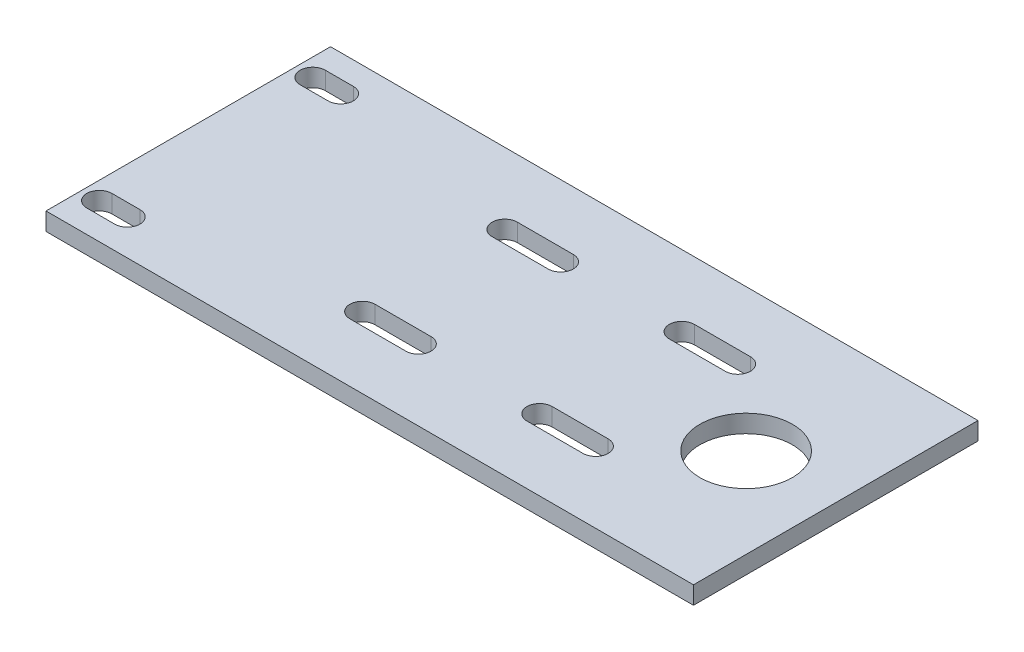
SolidWorks part; units mm, degrees
ref_plane "Front Plane" through (0, 0, 0) normal (0, 0, 1) x (1, 0, 0)
ref_plane "Top Plane" through (0, 0, 0) normal (0, 1, 0) x (1, 0, 0)
ref_plane "Right Plane" through (0, 0, 0) normal (1, 0, 0) x (0, 0, -1)
sketch "Sketch1" plane through (0, 0, 0) normal (0, 1, 0) x (1, 0, 0)
  line L0 (0, 50.8) -> (0, 0)
  line L1 (0, 0) -> (125, 0)
  line L3 (0, 50.8) -> (125, 50.8)
  line L4 (125, 0) -> (125, 50.8)
  dimension "D1" = 50.8
  dimension "D2" = 125
extrude "Boss-Extrude1" add sketch "Sketch1" along normal blind 3.175
sketch "Sketch2" plane through (0, 3.175, 0) normal (0, 1, 0) x (1, 0, 0)
  line L0 (125, 0) -> (125, 50.8) construction
  line L1 (125, 50.8) -> (0, 50.8) construction
  line L2 (125, 50.8) -> (0, 50.8) construction
  line L3 (0, 50.8) -> (0, 0) construction
  line L4 (99.6, 25.4) -> (80.425, 25.4) construction
  line L5 (80.425, 50.8) -> (80.425, 40.35) construction
  line L6 (0, 0) -> (125, 0) construction
  line L7 (3.175, 42.2) -> (8.175, 42.2)
  line L8 (3.175, 4.1) -> (8.175, 4.1)
  line L9 (3.175, 46.7) -> (8.175, 46.7)
  line L10 (3.175, 8.6) -> (8.175, 8.6)
  line L11 (80.425, 40.35) -> (85.425, 40.35)
  line L12 (80.425, 40.35) -> (75.425, 40.35)
  line L13 (48.8, 35.85) -> (43.8, 35.85)
  line L14 (48.8, 35.85) -> (53.8, 35.85)
  line L15 (48.8, 10.45) -> (43.8, 10.45)
  line L16 (48.8, 10.45) -> (53.8, 10.45)
  line L17 (48.8, 40.35) -> (43.8, 40.35)
  line L18 (48.8, 40.35) -> (53.8, 40.35)
  line L19 (48.8, 14.95) -> (43.8, 14.95)
  line L20 (48.8, 14.95) -> (53.8, 14.95)
  line L21 (80.425, 35.85) -> (85.425, 35.85)
  line L22 (80.425, 35.85) -> (75.425, 35.85)
  line L23 (80.425, 35.85) -> (80.425, 0) construction
  line L24 (80.425, 10.45) -> (75.425, 10.45)
  line L25 (80.425, 14.95) -> (75.425, 14.95)
  line L26 (80.425, 14.95) -> (85.425, 14.95)
  line L27 (80.425, 10.45) -> (85.425, 10.45)
  circle A0 centre (99.6, 25.4) radius 8.255
  arc A1 (3.175, 46.7) -> (3.175, 42.2) centre (3.175, 44.45) ccw
  arc A2 (3.175, 8.6) -> (3.175, 4.1) centre (3.175, 6.35) ccw
  arc A3 (8.175, 42.2) -> (8.175, 46.7) centre (8.175, 44.45) ccw
  arc A4 (8.175, 4.1) -> (8.175, 8.6) centre (8.175, 6.35) ccw
  arc A5 (43.8, 40.35) -> (43.8, 35.85) centre (43.8, 38.1) ccw
  arc A6 (43.8, 14.95) -> (43.8, 10.45) centre (43.8, 12.7) ccw
  arc A7 (75.425, 40.35) -> (75.425, 35.85) centre (75.425, 38.1) ccw
  arc A9 (53.8, 35.85) -> (53.8, 40.35) centre (53.8, 38.1) ccw
  arc A10 (53.8, 10.45) -> (53.8, 14.95) centre (53.8, 12.7) ccw
  arc A11 (85.425, 35.85) -> (85.425, 40.35) centre (85.425, 38.1) ccw
  arc A12 (75.425, 10.45) -> (75.425, 14.95) centre (75.425, 12.7) cw
  arc A13 (85.425, 14.95) -> (85.425, 10.45) centre (85.425, 12.7) cw
  point P20 (139.7, 91.3911)
  dimension "D1" = 25.4
  dimension "D3" = 16.51
  dimension "D5" = 3.175
  dimension "D4" = 6.35
  dimension "D2" = 25.4
extrude "Cut-Extrude1" cut sketch "Sketch2" against normal through all
sketch "Sketch3" plane through (0, 3.175, 0) normal (0, 1, 0) x (1, 0, 0)
  line L0 (0, 0) -> (125, 0) construction
  line L1 (125, 50.8) -> (115.6, 50.8)
  line L2 (125, 50.8) -> (125, 0)
  line L3 (125, 0) -> (115.6, 0)
  line L4 (115.6, 50.8) -> (115.6, 0)
extrude "Cut-Extrude2" cut sketch "Sketch3" against normal blind 10
